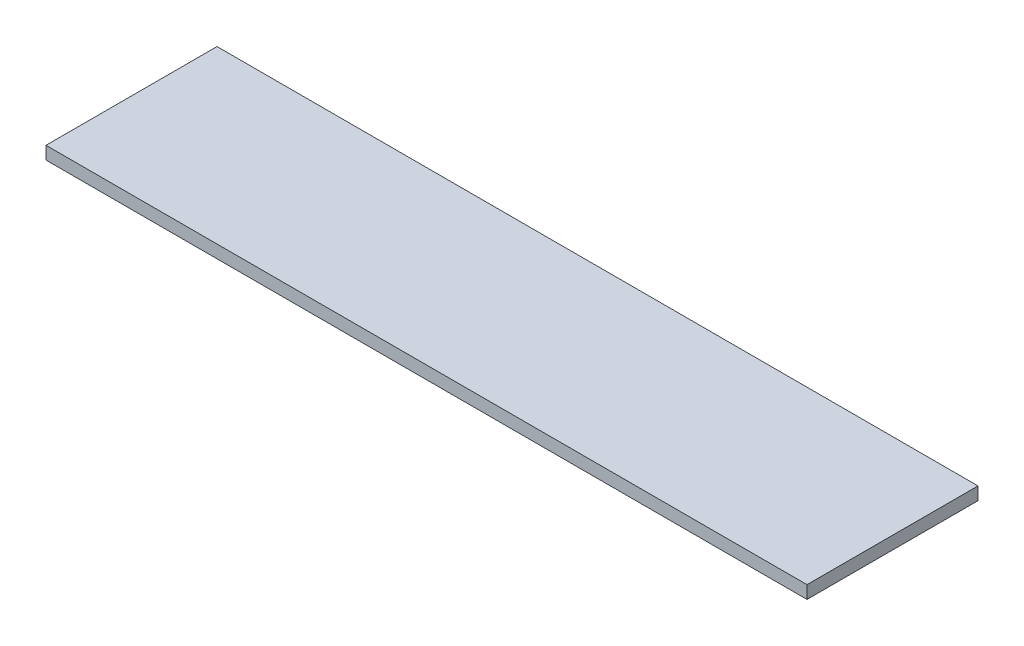
SolidWorks part; units mm, degrees
ref_plane "Front Plane" through (0, 0, 0) normal (0, 0, 1) x (1, 0, 0)
ref_plane "Top Plane" through (0, 0, 0) normal (0, 1, 0) x (1, 0, 0)
ref_plane "Right Plane" through (0, 0, 0) normal (1, 0, 0) x (0, 0, -1)
sketch "Sketch1" plane through (0, 0, 0) normal (0, 1, 0) x (1, 0, 0)
  line L1 (-44.5, -10) -> (44.5, -10)
  line L2 (-44.5, -10) -> (-44.5, 10)
  line L3 (-44.5, 10) -> (44.5, 10)
  line L4 (44.5, -10) -> (44.5, 10)
  line L5 (-44.5, -10) -> (44.5, 10) construction
  line L6 (-44.5, 10) -> (44.5, -10) construction
  point P0 (0, 0)
  dimension "D1" = 89
  dimension "D2" = 20
extrude "Boss-Extrude1" add sketch "Sketch1" along normal blind 1.5
